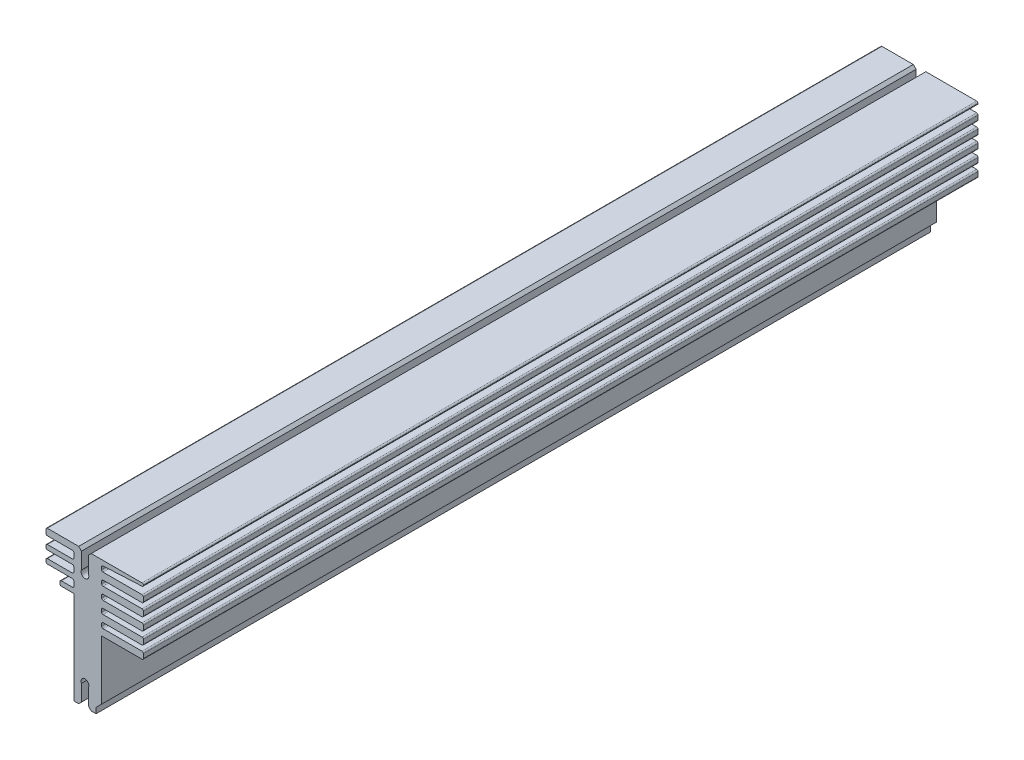
SolidWorks part; units mm, degrees
ref_plane "Спереди" through (0, 0, 0) normal (0, 0, 1) x (1, 0, 0)
ref_plane "Сверху" through (0, 0, 0) normal (0, 1, 0) x (1, 0, 0)
ref_plane "Справа" through (0, 0, 0) normal (1, 0, 0) x (0, 0, -1)
sketch "Эскиз1" plane through (0, 0, 0) normal (0, 0, 1) x (1, 0, 0)
  line L0 (0, 0) -> (0, 49) construction
  line L1 (0, 49) -> (-14, 49) construction
  line L2 (0, 49) -> (21, 49) construction
  line L3 (0, 0) -> (21, 0) construction
  line L4 (21, 0) -> (21, 49) construction
  line L5 (0, 0) -> (-14, 0) construction
  line L6 (-14, 0) -> (-14, 49) construction
  line L7 (-1.25, 0) -> (-1.25, 6.8695)
  line L8 (1.25, 0) -> (1.25, 6.8695)
  line L9 (-1.25, 0) -> (-4, 0)
  line L10 (1.25, 0) -> (4, 0)
  line L11 (4, 0) -> (4, 2)
  line L12 (4, 2) -> (6, 4)
  line L13 (-4, 0) -> (-4, 33.45)
  line L14 (-4, 33.45) -> (-9, 33.45)
  line L15 (-9, 33.45) -> (-9, 35.15)
  line L16 (-9, 35.15) -> (-4, 35.15)
  line L17 (-4, 35.15) -> (-4, 37.85)
  line L18 (-4, 37.85) -> (-14, 37.85)
  line L19 (-14, 37.85) -> (-14, 39.55)
  line L20 (-14, 39.55) -> (-4, 39.55)
  line L21 (-4, 39.55) -> (-4, 42.25)
  line L22 (-4, 42.25) -> (-14, 42.25)
  line L23 (-14, 42.25) -> (-14, 43.95)
  line L24 (-14, 43.95) -> (-4, 43.95)
  line L25 (-4, 43.95) -> (-4, 46.65)
  line L26 (-4, 46.65) -> (-14, 46.65)
  line L27 (-14, 46.65) -> (-14, 49)
  line L28 (-1.25, 49) -> (-1.25, 42.1169)
  line L29 (1.25, 49) -> (1.25, 42.1169)
  line L30 (-14, 49) -> (-1.25, 49)
  line L31 (1.25, 49) -> (21, 49)
  line L32 (6, 4) -> (6, 25.25)
  line L33 (6, 25.25) -> (21, 25.25)
  line L34 (21, 25.25) -> (21, 27.75)
  line L35 (21, 27.75) -> (6, 27.75)
  line L36 (6, 27.75) -> (6, 29.65)
  line L37 (6, 29.65) -> (21, 29.65)
  line L38 (21, 29.65) -> (21, 32.15)
  line L39 (21, 32.15) -> (6, 32.15)
  line L40 (6, 32.15) -> (6, 34.05)
  line L41 (6, 34.05) -> (21, 34.05)
  line L42 (21, 34.05) -> (21, 36.55)
  line L43 (21, 36.55) -> (6, 36.55)
  line L44 (6, 36.55) -> (6, 38.45)
  line L45 (6, 38.45) -> (21, 38.45)
  line L46 (21, 38.45) -> (21, 40.95)
  line L47 (21, 40.95) -> (6, 40.95)
  line L48 (6, 40.95) -> (6, 42.85)
  line L49 (6, 42.85) -> (21, 42.85)
  line L50 (21, 42.85) -> (21, 45.35)
  line L51 (21, 45.35) -> (6, 45.35)
  line L52 (6, 45.35) -> (6, 47.25)
  line L53 (21, 49) -> (21, 48)
  line L54 (6, 47.25) -> (21, 48)
  arc A1 (-1.25, 42.1169) -> (1.25, 42.1169) centre (0, 41.5) ccw
  arc A2 (1.25, 6.8695) -> (-1.25, 6.8695) centre (0, 7.5) ccw
  dimension "D4" = 2
  dimension "D7" = 21.25
  dimension "D1" = 21
  dimension "D2" = 14
  dimension "D3" = 49
  dimension "D5" = 33.45
extrude "Бобышка-Вытянуть1" add sketch "Эскиз1" along normal blind 299.9967
chamfer "Фаска1" distance 1 angle 45 1 edges at (-1.25, 0, 149.9984)
chamfer "Фаска2" distance 1 angle 45 1 edges at (1.25, 0, 149.9984)
fillet "Скругление1" radius 0.5 7 edges at (-14, 46.65, 149.9984) (-14, 43.95, 149.9984) (-14, 42.25, 149.9984) (-14, 39.55, 149.9984) (-14, 37.85, 149.9984) (-9, 35.15, 149.9984) (-9, 33.45, 149.9984)
fillet "Скругление2" radius 0.5 3 edges at (-4, 43.95, 149.9984) (-4, 39.55, 149.9984) (-4, 35.15, 149.9984)
fillet "Скругление3" radius 0.5 3 edges at (-4, 37.85, 149.9984) (-4, 42.25, 149.9984) (-4, 46.65, 149.9984)
fillet "Скругление4" radius 0.5 1 edges at (-14, 49, 149.9984)
fillet "Скругление5" radius 0.5 12 edges at (21, 25.25, 149.9984) (21, 27.75, 149.9984) (21, 29.65, 149.9984) (21, 32.15, 149.9984) (21, 34.05, 149.9984) (21, 36.55, 149.9984) (21, 38.45, 149.9984) (21, 40.95, 149.9984) (21, 42.85, 149.9984) (21, 48, 149.9984) (21, 45.35, 149.9984) (21, 49, 149.9984)
fillet "Скругление6" radius 0.5 5 edges at (6, 29.65, 149.9984) (6, 34.05, 149.9984) (6, 38.45, 149.9984) (6, 42.85, 149.9984) (6, 47.25, 149.9984)
fillet "Скругление7" radius 0.5 5 edges at (6, 27.75, 149.9984) (6, 32.15, 149.9984) (6, 36.55, 149.9984) (6, 40.95, 149.9984) (6, 45.35, 149.9984)
chamfer "Фаска4" distance 1 angle 45 1 edges at (-1.25, 49, 149.9984)
chamfer "Фаска5" distance 1 angle 45 1 edges at (1.25, 49, 149.9984)
